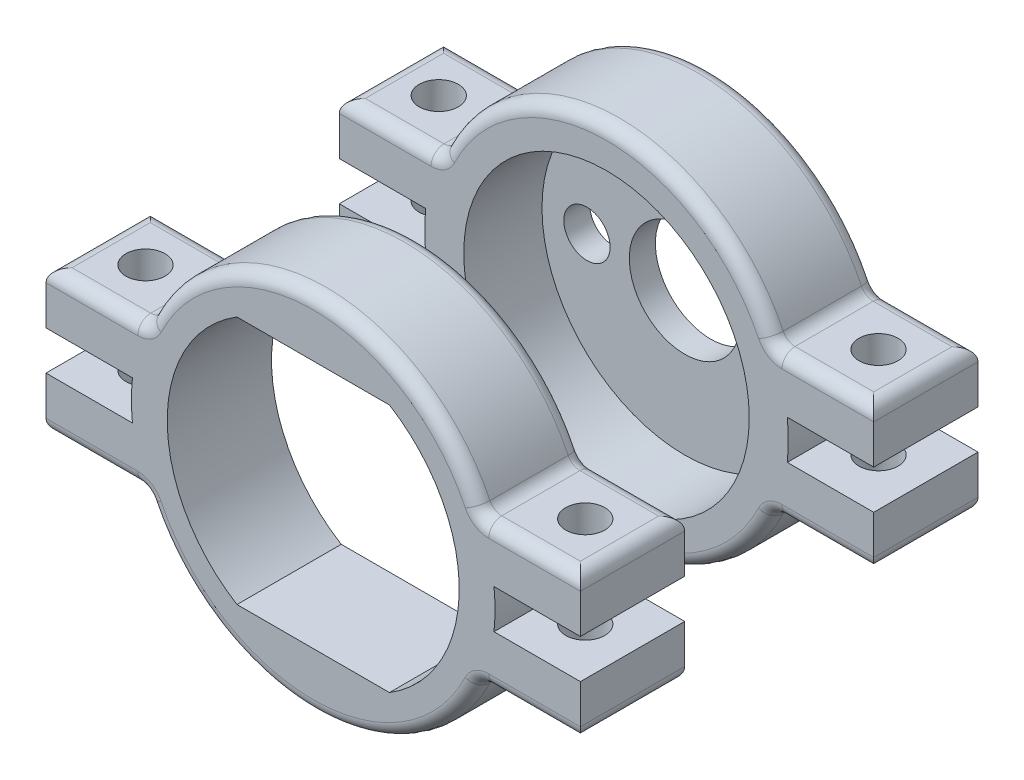
SolidWorks part; units mm, degrees
ref_plane "Alzado" through (0, 0, 0) normal (0, 0, 1) x (1, 0, 0)
ref_plane "Planta" through (0, 0, 0) normal (0, 1, 0) x (1, 0, 0)
ref_plane "Vista lateral" through (0, 0, 0) normal (1, 0, 0) x (0, 0, -1)
sketch "Croquis1" plane through (0, 0, 0) normal (0, 0, 1) x (1, 0, 0)
  line L0 (0, 1.5) -> (0, -1.5) construction
  line L1 (-13.8691, 1.5) -> (-24, 1.5)
  line L2 (-24, 1.5) -> (-24, 5.5)
  line L3 (-13.8691, -1.5) -> (-24, -1.5)
  line L4 (-24, 5.5) -> (-12.82, 5.5)
  line L5 (-24, -1.5) -> (-24, -5.5)
  line L6 (-24, -5.5) -> (-12.82, -5.5)
  line L7 (24, -5.5) -> (12.82, -5.5)
  line L8 (24, 5.5) -> (12.82, 5.5)
  line L9 (13.8691, -1.5) -> (24, -1.5)
  line L10 (13.8691, 1.5) -> (24, 1.5)
  line L11 (24, -1.5) -> (24, -5.5)
  line L12 (24, 1.5) -> (24, 5.5)
  arc A0 (12.82, 5.5) -> (-12.82, 5.5) centre (0, 0) ccw
  arc A1 (-13.8691, 1.5) -> (-13.8691, -1.5) centre (0, 0) ccw
  arc A2 (-12.82, -5.5) -> (12.82, -5.5) centre (0, 0) ccw
  arc A3 (13.8691, -1.5) -> (13.8691, 1.5) centre (0, 0) ccw
  dimension "D2" = 10.1309
  dimension "D3" = 10.1309
  dimension "D4" = 11.18
  dimension "D5" = 11.18
  dimension "D6" = 4
  dimension "D7" = 4
extrude "Saliente-Extruir1" add sketch "Croquis1" along normal blind 8
sketch "Croquis2" plane through (0, 0, 8) normal (0, 0, 1) x (1, 0, 0)
  circle A0 centre (0, 0) radius 10.95
  dimension "D1" = 21.9
extrude "Cortar-Extruir1" cut sketch "Croquis2" against normal blind 6
sketch "Croquis3" plane through (0, 0, 2) normal (0, 0, 1) x (1, 0, 0)
  line L0 (0, 10.95) -> (0, -10.95) construction
  line L1 (-10.95, 0) -> (10.95, 0) construction
  circle A0 centre (0, 0) radius 4.25
  circle A1 centre (0, 0) radius 10.95 construction
  circle A4 centre (-7.5, 0) radius 1.775
  circle A5 centre (7.5, 0) radius 1.775
  dimension "D1" = 8.5
  dimension "D2" = 3.55
  dimension "D3" = 3.55
  dimension "D4" = 7.5
  dimension "D5" = 7.5
extrude "Cortar-Extruir2" cut sketch "Croquis3" against normal blind 3.5
sketch "Croquis4" plane through (0, 0, 8) normal (0, 0, 1) x (1, 0, 0)
  line L2 (-12.82, 5.5) -> (-24, 5.5)
  line L3 (-24, 5.5) -> (-24, 1.5)
  line L4 (-24, 1.5) -> (-13.8691, 1.5)
  line L5 (-13.8691, -1.5) -> (-24, -1.5)
  line L6 (-24, -1.5) -> (-24, -5.5)
  line L7 (-24, -5.5) -> (-12.82, -5.5)
  line L8 (0, 10.95) -> (0, -10.95) construction
  line L9 (24, -5.5) -> (12.82, -5.5)
  line L10 (24, -1.5) -> (24, -5.5)
  line L11 (13.8691, -1.5) -> (24, -1.5)
  line L12 (24, 1.5) -> (13.8691, 1.5)
  line L13 (24, 5.5) -> (24, 1.5)
  line L14 (12.82, 5.5) -> (24, 5.5)
  arc A0 (-12.82, 5.5) -> (-13.8691, 1.5) centre (0, 0) ccw
  arc A1 (12.82, 5.5) -> (-12.82, 5.5) centre (0, 0) ccw construction
  arc A2 (-13.8691, -1.5) -> (-12.82, -5.5) centre (0, 0) ccw
  arc A3 (-13.8691, 1.5) -> (-13.8691, -1.5) centre (0, 0) ccw construction
  circle A4 centre (0, 0) radius 10.95 construction
  arc A5 (13.8691, -1.5) -> (12.82, -5.5) centre (0, 0) cw
  arc A6 (12.82, 5.5) -> (13.8691, 1.5) centre (0, 0) cw
extrude "Saliente-Extruir2" add sketch "Croquis4" along normal blind 14.5
sketch "Croquis6" plane through (0, 0, 22.5) normal (0, 0, 1) x (1, 0, 0)
  line L0 (-12.82, 5.5) -> (-24, 5.5)
  line L1 (-24, 5.5) -> (-24, 1.5)
  line L2 (-24, 1.5) -> (-13.8691, 1.5)
  line L4 (24, -1.5) -> (13.8691, -1.5)
  line L5 (24, -5.5) -> (24, -1.5)
  line L6 (12.82, 5.5) -> (24, 5.5)
  line L7 (24, 5.5) -> (24, 1.5)
  line L8 (24, 1.5) -> (13.8691, 1.5)
  line L9 (12.82, -5.5) -> (24, -5.5)
  line L10 (-24, -1.5) -> (-13.8691, -1.5)
  line L11 (-24, -5.5) -> (-24, -1.5)
  line L12 (-12.82, -5.5) -> (-24, -5.5)
  arc A0 (12.82, 5.5) -> (-12.82, 5.5) centre (0, 0) ccw
  arc A3 (12.82, -5.5) -> (-12.82, -5.5) centre (0, 0) cw
  arc A4 (-13.8691, 1.5) -> (-13.8691, -1.5) centre (0, 0) ccw
  arc A5 (13.8691, -1.5) -> (13.8691, 1.5) centre (0, 0) ccw
  dimension "D5" = 3
  dimension "D6" = 3
  dimension "D1" = 4
  dimension "D2" = 4
  dimension "D3" = 10.1309
  dimension "D4" = 11.18
  dimension "D7" = 4
  dimension "D8" = 11.18
  dimension "D9" = 4
extrude "Saliente-Extruir3" add sketch "Croquis6" along normal blind 8
sketch "Croquis7" plane through (0, 0, 30.5) normal (0, 0, 1) x (1, 0, 0)
  line L0 (-5.8487, 9.5516) -> (5.8487, 9.5516)
  line L1 (-5.8487, -9.5516) -> (5.8487, -9.5516)
  arc A0 (-5.8487, 9.5516) -> (-5.8487, -9.5516) centre (0, 0) ccw
  arc A1 (5.8487, -9.5516) -> (5.8487, 9.5516) centre (0, 0) ccw
  dimension "D1" = 11.2
  dimension "D4" = 11.2
  dimension "D2" = 11.6974
  dimension "D3" = 11.6974
extrude "Cortar-Extruir3" cut sketch "Croquis7" against normal blind 8
sketch "Croquis8" plane through (0, 5.5, 0) normal (0, 1, 0) x (1, 0, 0)
  line L0 (12.82, -30.5) -> (12.82, -22.5) construction
  line L1 (12.82, -22.5) -> (24, -22.5) construction
  line L2 (24, -30.5) -> (24, 0) construction
  line L3 (12.82, 0) -> (12.82, -8) construction
  line L4 (12.82, -22.5) -> (12.82, -8) construction
  line L5 (12.82, -8) -> (24, -8) construction
  line L6 (24, 0) -> (12.82, 0) construction
  line L7 (24, -30.5) -> (12.82, -30.5) construction
  line L8 (0, -4) -> (0, -26.5) construction
  circle A0 centre (16.87, -26.5) radius 1.5
  circle A1 centre (16.87, -4) radius 1.5
  circle A2 centre (-16.87, -4) radius 1.5
  circle A3 centre (-16.87, -26.5) radius 1.5
  dimension "D1" = 3
  dimension "D2" = 3
  dimension "D4" = 4.05
  dimension "D3" = 4.05
  dimension "D5" = 4
  dimension "D6" = 4
extrude "Cortar-Extruir4" cut sketch "Croquis8" against normal through all
sketch "Croquis9" plane through (0, 5.5, 0) normal (0, 1, 0) x (1, 0, 0)
  line L0 (0, 0) -> (0, -30.5) construction
  line L1 (24, 0) -> (12.82, 0) construction
  line L2 (24, -30.5) -> (20.5, -30.5)
  line L3 (24, -30.5) -> (24, 0)
  line L4 (24, 0) -> (20.5, 0)
  line L5 (20.5, -30.5) -> (20.5, 0)
  line L6 (-12.82, -30.5) -> (12.82, -30.5) construction
  line L7 (-20.5, -30.5) -> (-20.5, 0)
  line L8 (-24, 0) -> (-20.5, 0)
  line L9 (-24, -30.5) -> (-24, 0)
  line L10 (-24, -30.5) -> (-20.5, -30.5)
  dimension "D1" = 3.5
extrude "Cortar-Extruir6" cut sketch "Croquis9" against normal through all
sketch "Croquis10" plane through (0, 5.5, 0) normal (0, 1, 0) x (1, 0, 0)
  line L0 (-12.82, -8) -> (-20.5, -8)
  line L1 (-20.5, -30.5) -> (-20.5, 0) construction
  line L2 (-20.5, -8) -> (-20.5, -22.5)
  line L3 (-20.5, -22.5) -> (-12.82, -22.5)
  line L4 (-12.82, -22.5) -> (-12.82, -8)
  line L5 (12.82, -8) -> (20.5, -8)
  line L6 (20.5, 0) -> (20.5, -30.5) construction
  line L7 (20.5, -8) -> (20.5, -22.5)
  line L8 (20.5, -22.5) -> (12.82, -22.5)
  line L9 (12.82, -22.5) -> (12.82, -8)
extrude "Cortar-Extruir7" cut sketch "Croquis10" against normal through all
fillet "Redondeo3" radius 1 20 edges at (20.5, -5.5, 4) (16.66, -5.5, 8) (12.82, -5.5, 4) (16.66, -5.5, 0) (16.66, 5.5, 0) (20.5, 5.5, 4) (0, 13.95, 8) (-16.66, 5.5, 8) (0, -13.95, 8) (0, 13.95, 0) (12.82, 5.5, 4) (-12.82, 5.5, 4) (-16.66, 5.5, 0) (-16.66, -5.5, 8) (-20.5, -5.5, 4) (-16.66, -5.5, 0) (0, -13.95, 0) (-12.82, -5.5, 4) (-20.5, 5.5, 4) (16.66, 5.5, 8)
fillet "Redondeo4" radius 1 20 edges at (0, 13.95, 22.5) (12.82, 5.5, 26.5) (-12.82, 5.5, 26.5) (0, -13.95, 22.5) (-12.82, -5.5, 26.5) (12.82, -5.5, 26.5) (0, 13.95, 30.5) (-16.66, 5.5, 30.5) (0, -13.95, 30.5) (16.66, -5.5, 30.5) (16.66, 5.5, 30.5) (-16.66, -5.5, 30.5) (-20.5, -5.5, 26.5) (-20.5, 5.5, 26.5) (-16.66, -5.5, 22.5) (-16.66, 5.5, 22.5) (20.5, 5.5, 26.5) (20.5, -5.5, 26.5) (16.66, -5.5, 22.5) (16.66, 5.5, 22.5)
